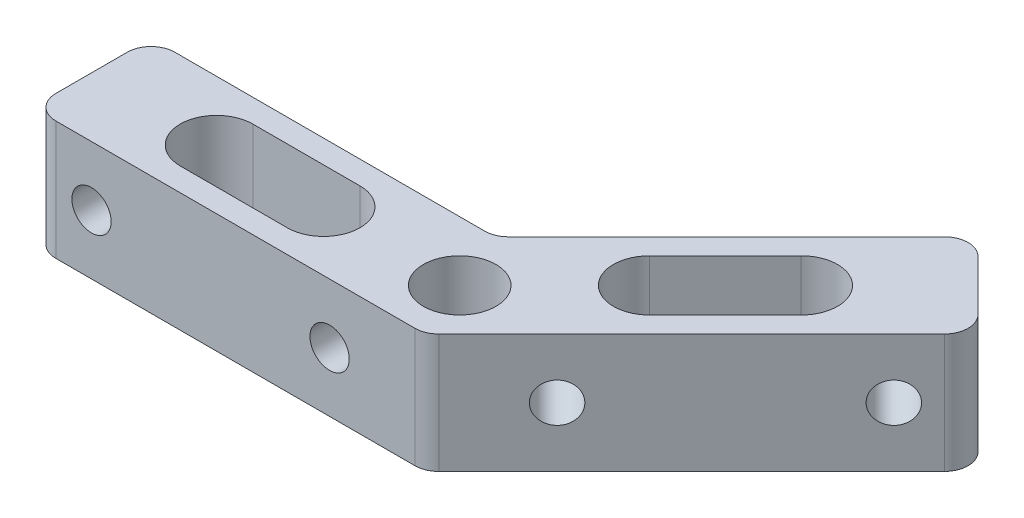
SolidWorks part; units mm, degrees
material "5052-H34"
ref_plane "正面" through (0, 0, 0) normal (0, 0, 1) x (1, 0, 0)
ref_plane "平面" through (0, 0, 0) normal (0, 1, 0) x (1, 0, 0)
ref_plane "右側面" through (0, 0, 0) normal (1, 0, 0) x (0, 0, -1)
sketch "ｽｹｯﾁ1" plane through (0, 0, 0) normal (0, 1, 0) x (1, 0, 0)
  line L0 (117.5, 107.5) -> (107.5, 107.5) construction
  line L1 (5, 5) -> (5, -5) construction
  line L2 (107.5, 137.5) -> (117.5, 137.5) construction
  line L3 (117.5, 137.5) -> (117.5, 100.3579) construction
  line L5 (12.1421, -5) -> (-25, -5) construction
  line L6 (-25, -5) -> (-25, 5) construction
  line L7 (-25, 5) -> (8, 5)
  line L9 (107.5, 104.5) -> (107.5, 137.5) construction
  line L10 (112.5, 137.5) -> (112.5, 0) construction
  line L11 (-25, 0) -> (112.5, 0) construction
  line L13 (12.1421, -5) -> (117.5, 100.3579) construction
  line L14 (107.5, 104.5) -> (8, 5) construction
  line L15 (57.75, 54.75) -> (64.8211, 47.6789) construction
  line L16 (61.2855, 51.2145) -> (10.0711, 0) construction
  line L17 (17.0914, 7.0203) -> (13.5558, 10.5558) construction
  line L18 (31.2335, 28.2335) -> (38.3046, 21.1624) construction
  line L19 (84.2665, 81.2665) -> (91.3376, 74.1954) construction
  line L20 (31.2335, 28.2335) -> (8, 5)
  line L21 (12.1421, -5) -> (38.3046, 21.1624) construction
  line L22 (-25, 5) -> (-25, 15)
  line L23 (-25, 15) -> (3.8579, 15)
  line L24 (3.8579, 15) -> (24.1624, 35.3046)
  line L25 (24.1624, 35.3046) -> (31.2335, 28.2335)
  circle A0 centre (0, 0) radius 2.15 construction
  circle A1 centre (112.5, 112.5) radius 2.15 construction
  circle A2 centre (-20, 0) radius 2.15 construction
  circle A3 centre (112.5, 132.5) radius 2.15 construction
  circle A5 centre (17.0914, 7.0203) radius 2.15 construction
  circle A6 centre (31.2335, 21.1624) radius 2.15 construction
  circle A7 centre (91.3376, 81.2665) radius 2.15 construction
  circle A8 centre (105.4797, 95.4086) radius 2.15 construction
  dimension "D1" = 112.5
  dimension "D2" = 112.5
  dimension "D3" = 4.3
  dimension "D4" = 20
  dimension "D5" = 20
  dimension "D10" = 5
  dimension "D11" = 5
  dimension "D14" = 85
  dimension "D15" = 20
  dimension "D16" = 5
  dimension "D20" = 9.9282
  dimension "D6" = 10
  dimension "D7" = 10
  dimension "D8" = 5
  dimension "D9" = 5
  dimension "D12" = 3
  dimension "D13" = 3
  dimension "D17" = 5
  dimension "D18" = 10
  dimension "D19" = 10
extrude "ﾎﾞｽ - 押し出し1" add sketch "ｽｹｯﾁ1" along normal blind 10
sketch "ｽｹｯﾁ2" plane through (0, 0, -5) normal (0, 0, 1) x (1, 0, 0)
  line L0 (-25, 5) -> (8, 5) construction
  line L1 (-25, 10) -> (-25, 0) construction
  line L2 (8, 10) -> (8, 0) construction
  circle A0 centre (-20, 5) radius 1.65
  circle A1 centre (0, 5) radius 1.65
  dimension "D1" = 3.3
  dimension "D2" = 5
  dimension "D3" = 20
extrude "ｶｯﾄ - 押し出し1" cut sketch "ｽｹｯﾁ2" against normal through all
sketch "ｽｹｯﾁ4" plane through (1.5, 0, 1.5) normal (0.7071, 0, 0.7071) x (0.7071, 0, -0.7071)
  line L0 (42.0495, 5) -> (9.1924, 5) construction
  line L1 (42.0495, 10) -> (42.0495, 0) construction
  line L2 (9.1924, 10) -> (9.1924, 0) construction
  circle A0 centre (37.0495, 5) radius 1.65
  circle A1 centre (17.0495, 5) radius 1.65
  dimension "D1" = 5
  dimension "D2" = 20
  dimension "D3" = 3.3
extrude "ｶｯﾄ - 押し出し3" cut sketch "ｽｹｯﾁ4" against normal up to surface (10 mm away) up to face at (14.0101, 5, -25.1523)
sketch "ｽｹｯﾁ5" plane through (0, 10, 0) normal (0, 1, 0) x (1, 0, 0)
  line L0 (-25, 10) -> (5.9289, 10) construction
  line L1 (-25, 15) -> (-25, 5) construction
  line L2 (5.9289, 10) -> (27.698, 31.769) construction
  line L3 (31.2335, 28.2335) -> (24.1624, 35.3046) construction
  line L4 (-14.5, 10) -> (-5.5, 10) construction
  line L5 (-14.5, 13.05) -> (-5.5, 13.05)
  line L6 (-14.5, 6.95) -> (-5.5, 6.95)
  line L7 (20.2733, 24.3444) -> (13.9094, 17.9804) construction
  line L8 (22.43, 22.1877) -> (16.0661, 15.8238)
  line L9 (18.1167, 26.5011) -> (11.7527, 20.1371)
  arc A0 (-14.5, 13.05) -> (-14.5, 6.95) centre (-14.5, 10) ccw
  arc A1 (-5.5, 6.95) -> (-5.5, 13.05) centre (-5.5, 10) ccw
  arc A2 (22.43, 22.1877) -> (18.1167, 26.5011) centre (20.2733, 24.3444) ccw
  arc A3 (11.7527, 20.1371) -> (16.0661, 15.8238) centre (13.9094, 17.9804) ccw
  circle A4 centre (5.9289, 10) radius 3.05
  point P7 (-10, 10)
  point P14 (17.0914, 21.1624)
  dimension "D1" = 3.05
  dimension "D4" = 10.5
  dimension "D5" = 9
  dimension "D6" = 6.1
  dimension "D2" = 10.5
  dimension "D3" = 9
extrude "ｶｯﾄ - 押し出し4" cut sketch "ｽｹｯﾁ5" against normal up to surface (10 mm away) up to face at (2.8756, 0, -17.2563)
fillet "ﾌｨﾚｯﾄ2" radius 2 6 edges at (31.2335, 5, -28.2335) (24.1624, 5, -35.3046) (8, 5, -5) (3.8579, 5, -15) (-25, 5, -5) (-25, 5, -15)
